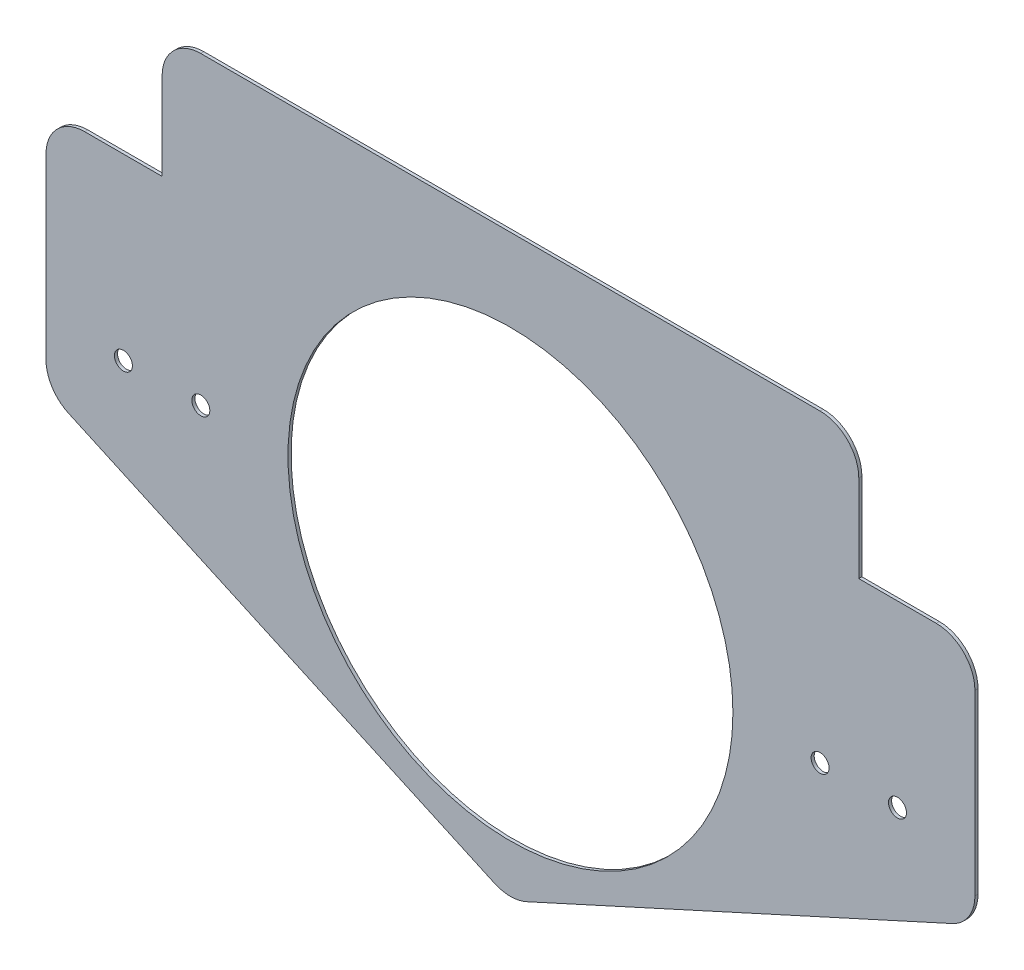
SolidWorks part; units mm, degrees
ref_plane "Front Plane" through (0, 0, 0) normal (0, 0, 1) x (1, 0, 0)
ref_plane "Top Plane" through (0, 0, 0) normal (0, 1, 0) x (1, 0, 0)
ref_plane "Right Plane" through (0, 0, 0) normal (1, 0, 0) x (0, 0, -1)
sketch "Sketch2" plane through (0, 0, 0) normal (0, 0, 1) x (1, 0, 0)
  line L0 (-25, 25) -> (25, 25) construction
  line L1 (0, 36.5) -> (0, -50) construction
  line L2 (-50.8, 0) -> (0, 0) construction
  line L3 (-57.15, 50) -> (57.15, 50)
  line L4 (-57.15, 50) -> (-57.15, -50)
  line L5 (-57.15, -50) -> (57.15, -50)
  line L6 (57.15, 50) -> (57.15, -50)
  line L7 (-57.15, 50) -> (57.15, -50) construction
  line L8 (-57.15, -50) -> (57.15, 50) construction
  line L9 (0, 0) -> (50.8, 0) construction
  line L10 (25, 25) -> (25, -25) construction
  line L11 (25, -25) -> (-25, -25) construction
  line L12 (-25, -25) -> (-25, 25) construction
  line L13 (-76.2, 3.9667) -> (-76.2, -3.9667)
  line L14 (57.15, 29.3667) -> (76.2, 29.3667)
  line L15 (57.15, 29.3667) -> (57.15, 3.9667)
  line L16 (57.15, 3.9667) -> (76.2, 3.9667)
  line L17 (76.2, 29.3667) -> (76.2, 3.9667)
  line L18 (57.15, -3.9667) -> (76.2, -3.9667)
  line L19 (57.15, -3.9667) -> (57.15, -29.3667)
  line L20 (57.15, -29.3667) -> (76.2, -29.3667)
  line L21 (76.2, -3.9667) -> (76.2, -29.3667)
  line L22 (-57.15, 29.3667) -> (-76.2, 29.3667)
  line L23 (-57.15, 29.3667) -> (-57.15, 3.9667)
  line L24 (-57.15, 3.9667) -> (-76.2, 3.9667)
  line L25 (-76.2, 29.3667) -> (-76.2, 3.9667)
  line L26 (-57.15, -3.9667) -> (-76.2, -3.9667)
  line L27 (-57.15, -3.9667) -> (-57.15, -29.3667)
  line L28 (-57.15, -29.3667) -> (-76.2, -29.3667)
  line L29 (-76.2, -3.9667) -> (-76.2, -29.3667)
  line L30 (76.2, 3.9667) -> (76.2, -3.9667)
  line L31 (0, -45) -> (57.15, -18.9667)
  line L32 (0, -45) -> (-57.15, -18.9667)
  line L33 (-63.5, 0) -> (-50.8, 0) construction
  line L34 (50.8, 0) -> (63.5, 0) construction
  line L35 (57.15, -18.9667) -> (76.2, -10.2889)
  line L36 (-57.15, -18.9667) -> (-76.2, -10.2889)
  circle A0 centre (0, 0) radius 36.5
  circle A11 centre (-50.8, 0) radius 1.475
  circle A12 centre (50.8, 0) radius 1.475
  circle A13 centre (63.5, 0) radius 1.475
  circle A14 centre (-63.5, 0) radius 1.475
  point P16 (0, 25)
  point P17 (25, 0)
  point P35 (-76.2, 16.6667)
  point P36 (-76.2, -16.6667)
  dimension "D1" = 73
  dimension "D11" = 2.95
  dimension "D3" = 114.3
  dimension "D10" = 100
  dimension "D12" = 50.8
  dimension "D2" = 50
  dimension "D4" = 33.3333
  dimension "D5" = 33.3333
  dimension "D6" = 19.05
  dimension "D7" = 25.4
  dimension "D8" = 12.7
  dimension "D9" = 15
  dimension "D13" = 5
extrude "Boss-Extrude1" add sketch "Sketch2" along normal blind 0.508 contours L32 L31 L6 L3 L4 A12 A11 A0 | L22 L25 L24 L4 | L26 L4 L24 L13 A14 | L36 L4 L26 L29 | L6 L35 L21 L18 | L30 L16 L6 L18 A13 | L17 L14 L6 L16
fillet "Fillet1" radius 6.35 7 edges at (-57.15, 50, 0.254) (57.15, 50, 0.254) (76.2, 29.3667, 0.254) (-76.2, 29.3667, 0.254) (0, -45, 0.254) (-76.2, -10.2889, 0.254) (76.2, -10.2889, 0.254)
equation "\"D5@Sketch2\"=\"D4@Sketch2\""
